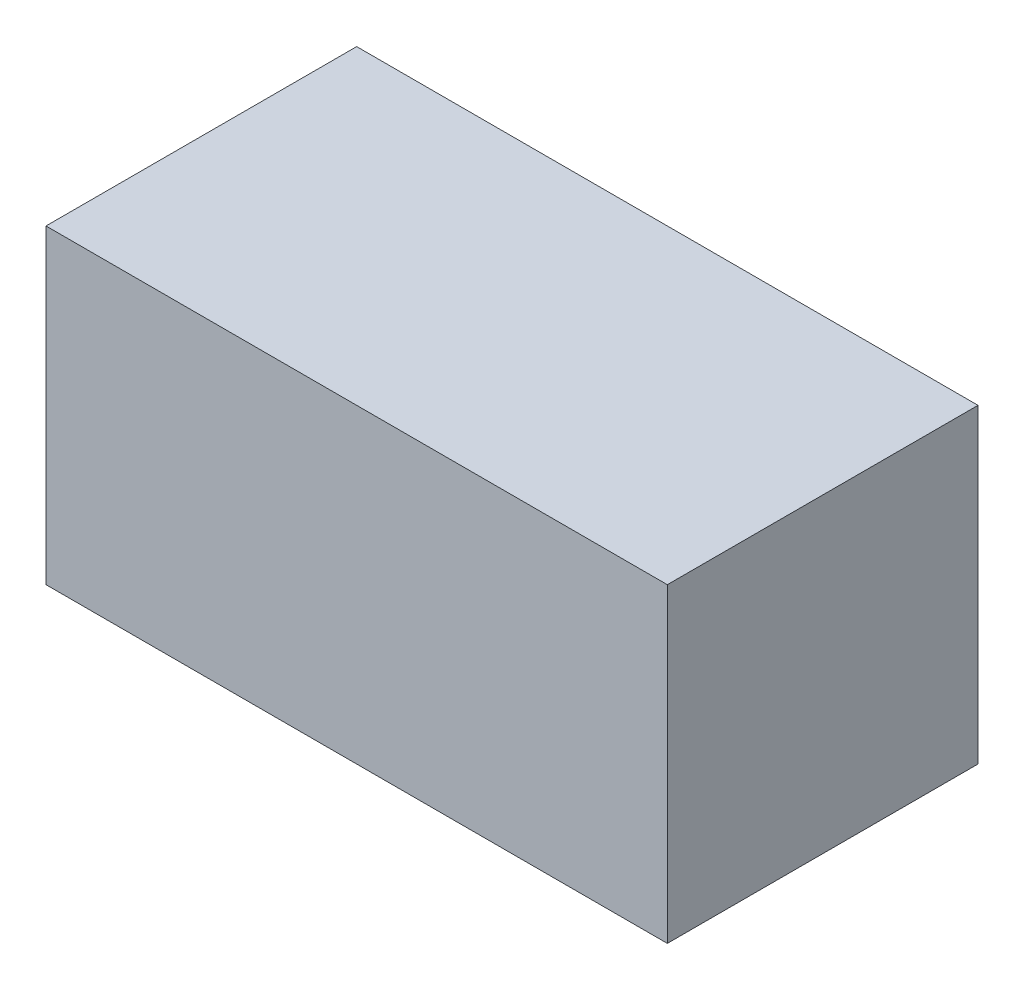
SolidWorks part; units mm, degrees
material "ABS"
ref_plane "Front Plane" through (0, 0, 0) normal (0, 0, 1) x (1, 0, 0)
ref_plane "Top Plane" through (0, 0, 0) normal (0, 1, 0) x (1, 0, 0)
ref_plane "Right Plane" through (0, 0, 0) normal (1, 0, 0) x (0, 0, -1)
sketch "Sketch1" plane through (0, 0, 0) normal (0, 0, 1) x (1, 0, 0)
  line L1 (-30, -15) -> (30, -15)
  line L2 (-30, -15) -> (-30, 15)
  line L3 (-30, 15) -> (30, 15)
  line L4 (30, -15) -> (30, 15)
  line L5 (0, 15) -> (0, -15) construction
  line L6 (-30, 0) -> (30, 0) construction
  point P16 (0, 0)
extrude "Boss-Extrude1" add sketch "Sketch1" along normal blind 30
sketch "Sketch2" plane through (0, 0, 0) normal (0, 0, 1) x (1, 0, 0)
  line L0 (-30, -15) -> (30, -15) construction
  line L1 (-10, -15) -> (10, -15)
  line L2 (-10, -15) -> (-10, 15)
  line L3 (-10, 15) -> (10, 15)
  line L4 (10, -15) -> (10, 15)
  line L5 (0, 15) -> (0, -15) construction
  line L6 (-10, 0) -> (10, 0) construction
  line L7 (30, 15) -> (-30, 15) construction
  point P20 (0, 0)
sketch "Sketch3" plane through (0, 0, 0) normal (0, 0, 1) x (1, 0, 0)
  line L1 (-28.5, -13.5) -> (-11.5, -13.5)
  line L2 (-28.5, -13.5) -> (-28.5, 13.5)
  line L3 (-28.5, 13.5) -> (-11.5, 13.5)
  line L4 (-11.5, -13.5) -> (-11.5, 13.5)
  line L5 (-20, 13.5) -> (-20, -13.5) construction
  line L6 (-28.5, 0) -> (-11.5, 0) construction
  line L7 (11.5, -13.5) -> (28.5, -13.5)
  line L8 (11.5, -13.5) -> (11.5, 13.5)
  line L9 (11.5, 13.5) -> (28.5, 13.5)
  line L10 (28.5, -13.5) -> (28.5, 13.5)
  line L11 (20, 13.5) -> (20, -13.5) construction
  line L12 (11.5, 0) -> (28.5, 0) construction
  point P16 (-20, 0)
  point P25 (20, 0)
sketch "Sketch4" plane through (0, 0, 0) normal (0, 0, 1) x (1, 0, 0)
  line L0 (-28.5, -13.5) -> (-11.5, -13.5) construction
  line L1 (-16.125, -13.5) -> (-14.625, -13.5)
  line L2 (-16.125, -13.5) -> (-16.125, 11.5)
  line L3 (-16.125, 11.5) -> (-14.625, 11.5)
  line L4 (-14.625, -13.5) -> (-14.625, 11.5)
  line L5 (-15.375, 11.5) -> (-15.375, -13.5) construction
  line L6 (-16.125, -1) -> (-14.625, -1) construction
  line L7 (-28.5, 13.5) -> (-11.5, 13.5) construction
  line L8 (-20.75, -11.5) -> (-19.25, -11.5)
  line L9 (-20.75, -11.5) -> (-20.75, 13.5)
  line L10 (-20.75, 13.5) -> (-19.25, 13.5)
  line L11 (-19.25, -11.5) -> (-19.25, 13.5)
  line L12 (-20, 13.5) -> (-20, -11.5) construction
  line L13 (-20.75, 1) -> (-19.25, 1) construction
  line L14 (11.5, -13.5) -> (28.5, -13.5) construction
  line L15 (-25.375, -13.5) -> (-23.875, -13.5)
  line L16 (-25.375, -13.5) -> (-25.375, 11.5)
  line L17 (-25.375, 11.5) -> (-23.875, 11.5)
  line L18 (-23.875, -13.5) -> (-23.875, 11.5)
  line L19 (-24.625, 11.5) -> (-24.625, -13.5) construction
  line L20 (-25.375, -1) -> (-23.875, -1) construction
  line L21 (14.625, -13.5) -> (16.125, -13.5)
  line L22 (14.625, -13.5) -> (14.625, 11.5)
  line L23 (14.625, 11.5) -> (16.125, 11.5)
  line L24 (16.125, -13.5) -> (16.125, 11.5)
  line L25 (15.375, 11.5) -> (15.375, -13.5) construction
  line L26 (14.625, -1) -> (16.125, -1) construction
  line L27 (11.5, 13.5) -> (28.5, 13.5) construction
  line L28 (19.25, -11.5) -> (20.75, -11.5)
  line L29 (19.25, -11.5) -> (19.25, 13.5)
  line L30 (19.25, 13.5) -> (20.75, 13.5)
  line L31 (20.75, -11.5) -> (20.75, 13.5)
  line L32 (20, 13.5) -> (20, -11.5) construction
  line L33 (19.25, 1) -> (20.75, 1) construction
  line L35 (23.875, -13.5) -> (25.375, -13.5)
  line L36 (23.875, -13.5) -> (23.875, 11.5)
  line L37 (23.875, 11.5) -> (25.375, 11.5)
  line L38 (25.375, -13.5) -> (25.375, 11.5)
  line L39 (24.625, 11.5) -> (24.625, -13.5) construction
  line L40 (23.875, -1) -> (25.375, -1) construction
  point P16 (-15.375, -1)
  point P31 (-20, 1)
  point P38 (-24.625, -1)
  point P47 (15.375, -1)
  point P62 (20, 1)
  point P69 (24.625, -1)
extrude "Boss-Extrude2" add sketch "Sketch4" along normal blind 28.5
sketch "Sketch5" plane through (0, 0, 0) normal (0, 0, 1) x (1, 0, 0)
  line L0 (-10, -15) -> (-10, 15) construction
  line L1 (-11.5, -13.5) -> (-10, -13.5)
  line L2 (-11.5, -13.5) -> (-11.5, -11.5)
  line L3 (-11.5, -11.5) -> (-10, -11.5)
  line L4 (-10, -13.5) -> (-10, -11.5)
  line L5 (-10.75, -11.5) -> (-10.75, -13.5) construction
  line L6 (-11.5, -12.5) -> (-10, -12.5) construction
  line L7 (10, -15) -> (10, 15) construction
  line L8 (10, -13.5) -> (11.5, -13.5)
  line L9 (10, -13.5) -> (10, -11.5)
  line L10 (10, -11.5) -> (11.5, -11.5)
  line L11 (11.5, -13.5) -> (11.5, -11.5)
  line L12 (10.75, -11.5) -> (10.75, -13.5) construction
  line L13 (10, -12.5) -> (11.5, -12.5) construction
  line L14 (11.5, -13.5) -> (11.5, 13.5) construction
  point P20 (-10.75, -12.5)
  point P32 (10.75, -12.5)
equation "\"W_cell\" = 60mm"
equation "\"H_cell\" = 30mm"
equation "\"D_cell\" = 30mm"
equation "\"W_airway\" = 20mm"
equation "\"t_wall\" = 1.5mm"
equation "\"w_slit_entry\" = 2.0mm"
equation "\"N_passes\" = 4"
equation "\"W_chamber\" = (\"W_cell\" - \"W_airway\") / 2"
equation "\"w_slit\" = (\"W_chamber\" - (\"N_passes\" + 1) * \"t_wall\") / \"N_passes\""
equation "\"L_baffle\" = \"H_cell\" - (2 * \"t_wall\") - \"w_slit_entry\""
equation "\"L_waveguide\" = 100mm"
